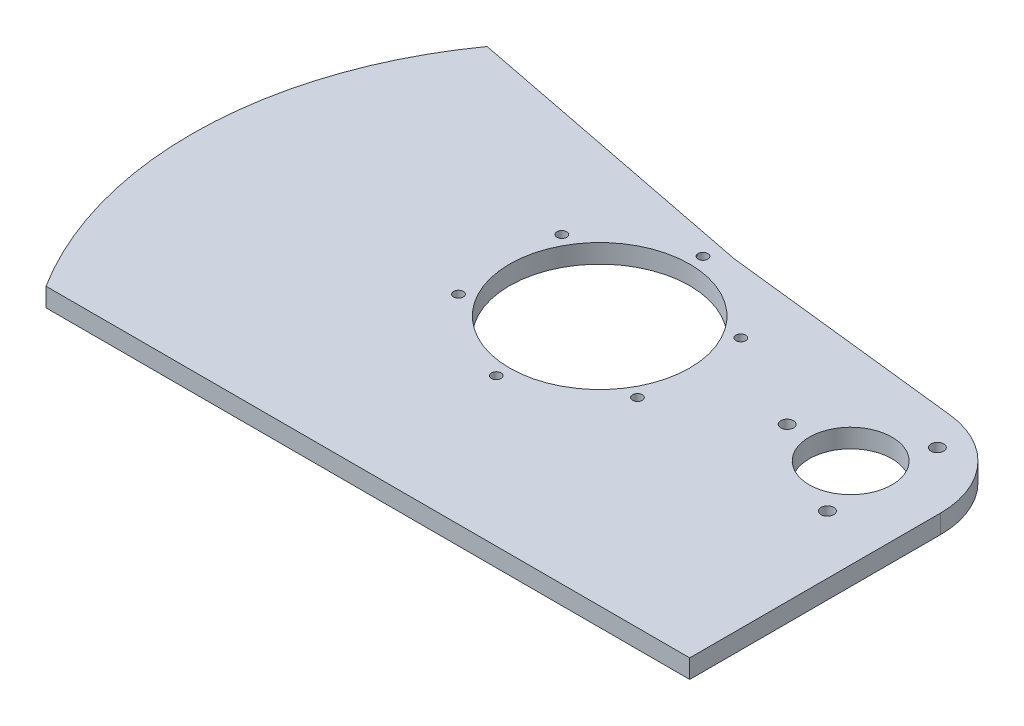
SolidWorks part; units mm, degrees
material "6061 Alloy"
ref_plane "Front Plane" through (0, 0, 0) normal (0, 0, 1) x (1, 0, 0)
ref_plane "Top Plane" through (0, 0, 0) normal (0, 1, 0) x (1, 0, 0)
ref_plane "Right Plane" through (0, 0, 0) normal (1, 0, 0) x (0, 0, -1)
sketch "Sketch1" plane through (0, 0, 0) normal (0, 1, 0) x (1, 0, 0)
  line L0 (4.4706, 39.7494) -> (88.4088, 30.3089)
  line L1 (-40, 40) -> (115.5, 40)
  line L2 (-40, 40) -> (-40, -85)
  line L3 (-40, -85) -> (115.5, -85)
  line L4 (115.5, 40) -> (115.5, -85)
  line L5 (-40, 40) -> (115.5, -85) construction
  line L6 (-40, -85) -> (115.5, 40) construction
  line L7 (-98.1071, 60) -> (7.6972, 39.2524)
  line L8 (-40, -85) -> (-102.5, -85)
  circle A0 centre (0, 0) radius 40
  circle A1 centre (0, 0) radius 30.5
  circle A2 centre (85, 0) radius 14
  circle A3 centre (85, 0) radius 30.5
  circle A5 centre (0, 0) radius 115 construction
  arc A6 (-98.1071, 60) -> (-102.5, -85) centre (7.5308, -15.7669) ccw
  point P4 (37.75, -22.5)
  point P18 (0, 0)
  dimension "D3" = 80
  dimension "D4" = 61
  dimension "D5" = 61
  dimension "D6" = 28
  dimension "D2" = 230
  dimension "D8" = 130
  dimension "D1" = 85
  dimension "D7" = 85
  dimension "D9" = 62.5
  dimension "D10" = 20
extrude "Boss-Extrude1" add sketch "Sketch1" along normal mid plane 6.35
hole_wizard "M4x0.7 Tapped Hole1" positions "Sketch4" profile "Sketch5" tap size "M4x0.7" standard "ANSI Metric" end condition up to next
sketch "Sketch4" plane through (0, 3.175, 0) normal (0, 1, 0) x (1, 0, 0)
  line L0 (0, 0) -> (0, 35)
  line L1 (0, 0) -> (30.3109, 17.5)
  line L2 (0, 0) -> (30.3109, -17.5)
  line L3 (0, 0) -> (0, -35)
  line L4 (0, 0) -> (-30.3109, -17.5)
  line L5 (0, 0) -> (-30.3109, 17.5)
  point P5 (0, 35)
  point P16 (30.3109, 17.5)
  point P17 (30.3109, -17.5)
  point P18 (0, -35)
  point P19 (-30.3109, -17.5)
  point P20 (-30.3109, 17.5)
  dimension "D1" = 35
  dimension "D2" = 6
sketch "Sketch5" plane through (-30.3109, 3.175, -17.5) normal (1, 0, 0) x (0, 0, 1)
  line L0 (0, 0) -> (0, 6.35)
  line L1 (0, 6.35) -> (1.65, 6.35)
  line L2 (1.65, 6.35) -> (1.65, 0)
  line L5 (1.65, 0) -> (0, 0)
  line L11 (0, -6.35) -> (0, 107.95) construction
  dimension "Thru Tap Drill Dia." = 3.3
  dimension "Thru Tap Drill Depth" = 6.35
cosmetic thread "Hole Thread1" parameters "D2"=4
cosmetic thread "Hole Thread2" parameters "D2"=4
cosmetic thread "Hole Thread3" parameters "D2"=4
cosmetic thread "Hole Thread4" parameters "D2"=4
cosmetic thread "Hole Thread5" parameters "D2"=4
cosmetic thread "Hole Thread6" parameters "D2"=4
hole_wizard "M4 Clearance Hole1" positions "Sketch6" profile "Sketch7" hole size "M4" standard "ANSI Metric" end condition up to next
sketch "Sketch6" plane through (0, 3.175, 0) normal (0, 1, 0) x (1, 0, 0)
  line L0 (85, 0) -> (95.75, 18.6195)
  line L1 (85, 0) -> (95.75, -18.6195)
  line L2 (85, 0) -> (63.5, 0)
  point P2 (95.75, 18.6195)
  point P10 (95.75, -18.6195)
  point P11 (63.5, 0)
  dimension "D1" = 21.5
  dimension "D2" = 3
sketch "Sketch7" plane through (63.5, 3.175, 0) normal (1, 0, 0) x (0, 0, 1)
  line L0 (0, 0) -> (0, 6.35)
  line L1 (0, 6.35) -> (2.15, 6.35)
  line L2 (2.15, 6.35) -> (2.15, 0)
  line L5 (2.15, 0) -> (0, 0)
  line L11 (0, -6.35) -> (0, 107.95) construction
  dimension "Thru Hole Dia." = 4.3
  dimension "Thru Hole Depth" = 6.35
